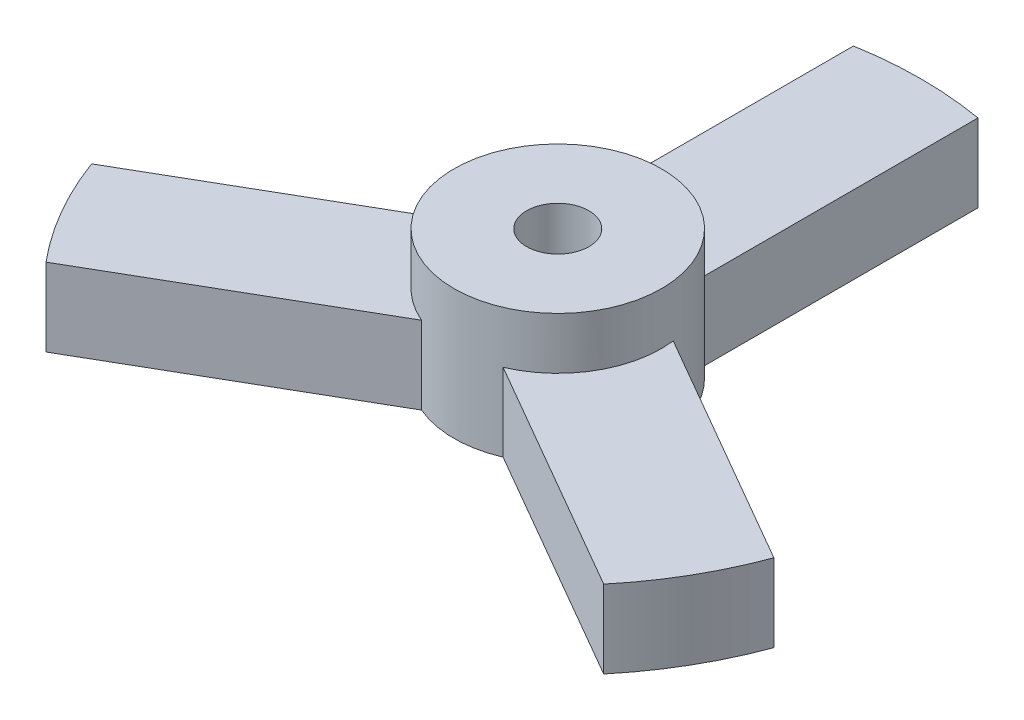
SolidWorks part; units mm, degrees
ref_plane "Front Plane" through (0, 0, 0) normal (0, 0, 1) x (1, 0, 0)
ref_plane "Top Plane" through (0, 0, 0) normal (0, 1, 0) x (1, 0, 0)
ref_plane "Right Plane" through (0, 0, 0) normal (1, 0, 0) x (0, 0, -1)
sketch "Sketch1" plane through (0, 0, 0) normal (0, 1, 0) x (1, 0, 0)
  line L0 (-6, 34.4819) -> (-6, 8)
  line L1 (6, 34.4819) -> (6, 8)
  line L2 (32.8622, -12.0448) -> (9.9282, 1.1962)
  line L3 (26.8622, -22.4371) -> (3.9282, -9.1962)
  line L4 (-26.8622, -22.4371) -> (-3.9282, -9.1962)
  line L5 (-32.8622, -12.0448) -> (-9.9282, 1.1962)
  circle A0 centre (0, 0) radius 35 construction
  circle A1 centre (0, 0) radius 10 construction
  arc A2 (-6, 34.4819) -> (6, 34.4819) centre (0, 0) cw
  arc A3 (32.8622, -12.0448) -> (26.8622, -22.4371) centre (0, 0) cw
  arc A4 (-26.8622, -22.4371) -> (-32.8622, -12.0448) centre (0, 0) cw
  arc A5 (6, 8) -> (9.9282, 1.1962) centre (0, 0) cw
  arc A6 (-3.9282, -9.1962) -> (3.9282, -9.1962) centre (0, 0) ccw
  arc A7 (-9.9282, 1.1962) -> (-6, 8) centre (0, 0) cw
  circle A8 centre (0, 0) radius 3.2 construction
  point P20 (0, 0)
  dimension "D1" = 70
  dimension "D2" = 20
  dimension "D4" = 3
  dimension "D5" = 6.4
  dimension "D3" = 12
extrude "Boss-Extrude1" add sketch "Sketch1" along normal blind 7.5
sketch "Sketch2" plane through (0, 7.5, 0) normal (0, 1, 0) x (1, 0, 0)
  circle A0 centre (0, 0) radius 10
  dimension "D1" = 20
extrude "Boss-Extrude2" add sketch "Sketch2" along normal blind 5
sketch "Sketch3" plane through (0, 0, 0) normal (0, 0, 1) x (1, 0, 0)
  line L0 (0, 0) -> (0, 12.5)
  line L1 (-3.9282, 0) -> (3.9282, 0) construction
  line L2 (10, 12.5) -> (-10, 12.5) construction
  line L3 (0, 12.5) -> (3, 12.5)
  line L4 (3, 12.5) -> (3, 1.7321)
  line L5 (3, 1.7321) -> (6, 0)
  line L6 (3.9282, 0) -> (26.8622, 0) construction
  line L7 (6, 0) -> (0, 0)
  point P6 (1.9034, 2.3652)
  dimension "D1" = 60
  dimension "D2" = 6
  dimension "D3" = 3
revolve "Cut-Revolve1" cut sketch "Sketch3" angle 360 about L0
